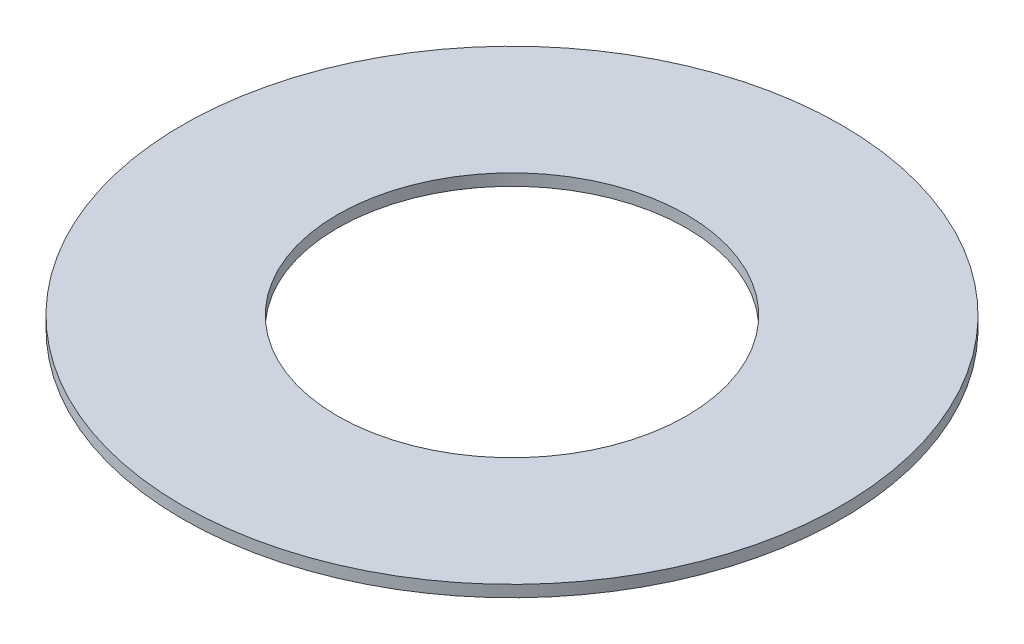
SolidWorks part; units mm, degrees
material "Corrugated Paper"
ref_plane "Front" through (0, 0, 0) normal (0, 0, 1) x (1, 0, 0)
ref_plane "Top" through (0, 0, 0) normal (0, 1, 0) x (1, 0, 0)
ref_plane "Right" through (0, 0, 0) normal (1, 0, 0) x (0, 0, -1)
sketch "Sketch1" plane through (0, 0, 0) normal (0, 1, 0) x (1, 0, 0)
  circle A0 centre (0, 0) radius 4.5
  circle A1 centre (0, 0) radius 8.5
  dimension "D1" = 9
  dimension "D2" = 17
extrude "Boss-Extrude1" add sketch "Sketch1" along normal mid plane 0.3
